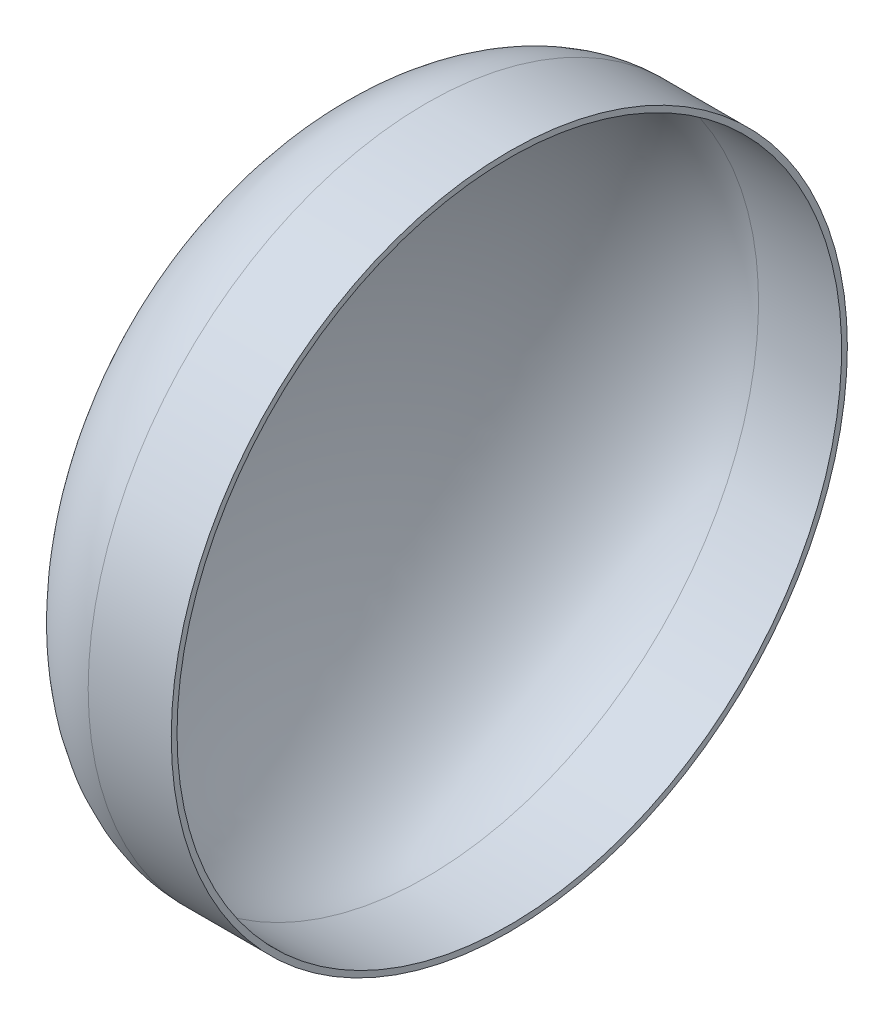
SolidWorks part; units mm, degrees
material "Простая углеродистая сталь"
ref_plane "Спереди" through (0, 0, 0) normal (0, 0, 1) x (1, 0, 0)
ref_plane "Сверху" through (0, 0, 0) normal (0, 1, 0) x (1, 0, 0)
ref_plane "Справа" through (0, 0, 0) normal (1, 0, 0) x (0, 0, -1)
sketch "Эскиз1" plane through (0, 0, 0) normal (0, 0, 1) x (1, 0, 0)
  line L0 (-57.5, 0) -> (28.75, 0)
  line L1 (0, 115) -> (0, 0)
  line L3 (28.75, 0) -> (28.75, 115)
  line L4 (28.75, 115) -> (0, 115)
  line L5 (0, 115) -> (-0.8605, 114.6914)
  ellipse E0 centre (0, 0) end of major axis (0, -115) minor radius 57.5 (0, 115) -> (-57.5, 0) ccw
revolve "Повернуть2" add sketch "Эскиз1" angle 360 about L0
shell "Оболочка2" thickness 2
